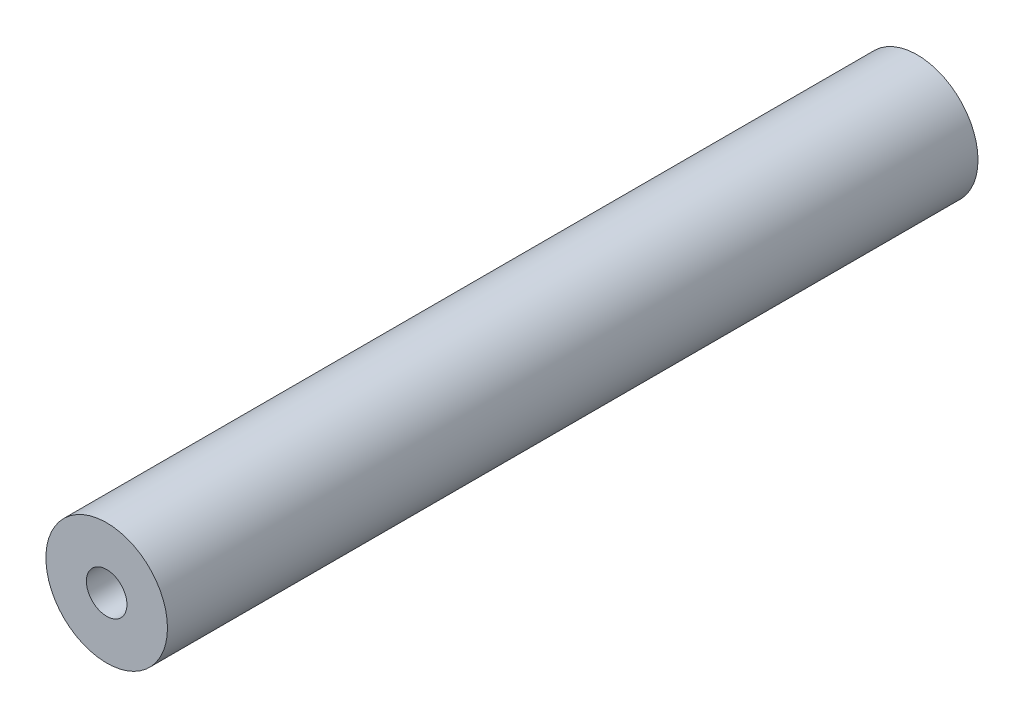
SolidWorks part; units mm, degrees
ref_plane "前视基准面" through (0, 0, 0) normal (0, 0, 1) x (1, 0, 0)
ref_plane "上视基准面" through (0, 0, 0) normal (0, 1, 0) x (1, 0, 0)
ref_plane "右视基准面" through (0, 0, 0) normal (1, 0, 0) x (0, 0, -1)
sketch "草图1" plane through (0, 0, 0) normal (0, 0, 1) x (1, 0, 0)
  circle A0 centre (0, 0) radius 7.5
  circle A1 centre (0, 0) radius 2.5
  dimension "D1" = 15
  dimension "D2" = 5
extrude "凸台-拉伸1" add sketch "草图1" along normal blind 100
